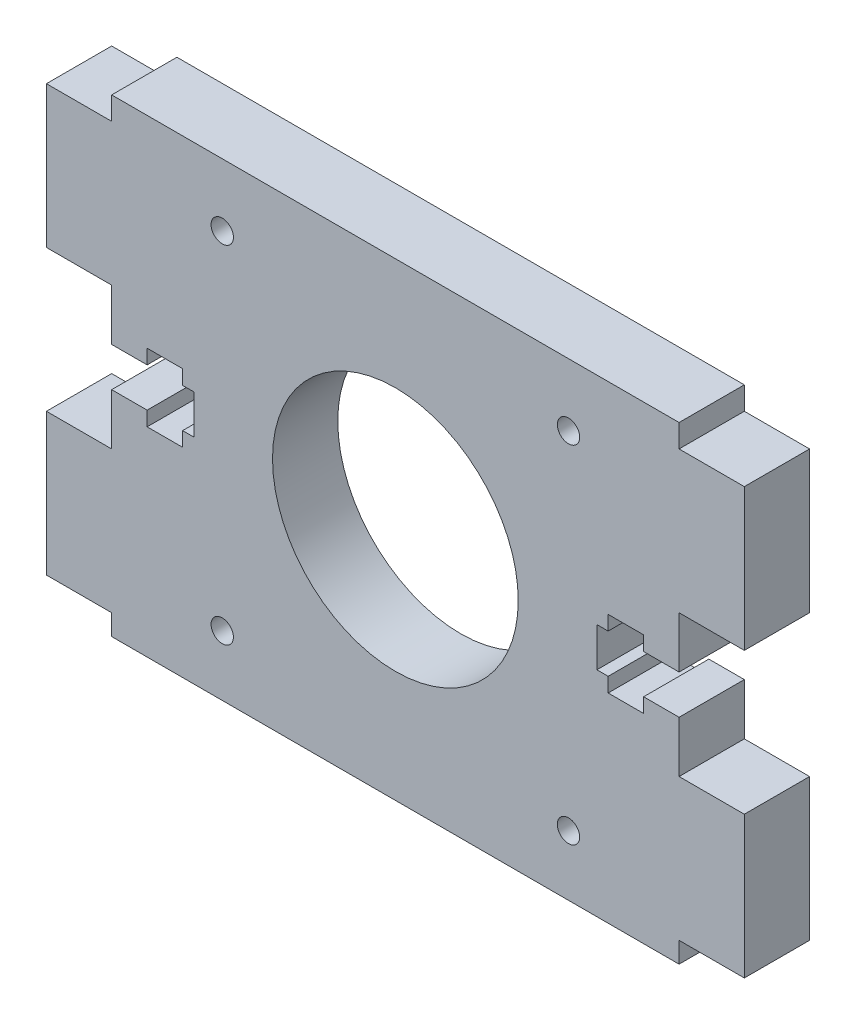
SolidWorks part; units mm, degrees
ref_plane "Front Plane" through (0, 0, 0) normal (0, 0, 1) x (1, 0, 0)
ref_plane "Top Plane" through (0, 0, 0) normal (0, 1, 0) x (1, 0, 0)
ref_plane "Right Plane" through (0, 0, 0) normal (1, 0, 0) x (0, 0, -1)
sketch "Sketch1" plane through (0, 0, 0) normal (0, 0, 1) x (1, 0, 0)
  line L0 (25.4, -0.1) -> (-25.4, -0.1) construction
  line L1 (25.4, -21) -> (-25.4, -21)
  line L2 (25.4, -21) -> (25.4, -19.15)
  line L3 (25.4, 21) -> (-25.4, 21)
  line L4 (-25.4, -6.45) -> (-25.4, 6.25)
  line L5 (25.4, -21) -> (-25.4, 21) construction
  line L6 (25.4, 21) -> (-25.4, -21) construction
  line L7 (0, 21) -> (0, -21) construction
  line L8 (-25.4, 18.95) -> (-25.4, 21)
  line L9 (-31.242, 6.25) -> (-25.4, 6.25)
  line L10 (-31.242, 6.25) -> (-31.242, 18.95)
  line L11 (-31.242, 18.95) -> (-25.4, 18.95)
  line L12 (-31.242, -19.15) -> (-25.4, -6.45) construction
  line L13 (-31.242, 6.25) -> (-25.4, 18.95) construction
  line L14 (-31.242, 18.95) -> (-25.4, 6.25) construction
  line L15 (-31.242, -6.45) -> (-25.4, -19.15) construction
  line L16 (-31.242, -19.15) -> (-25.4, -19.15)
  line L17 (-31.242, -6.45) -> (-31.242, -19.15)
  line L18 (-31.242, -6.45) -> (-25.4, -6.45)
  line L19 (-25.4, -21) -> (-25.4, -19.15)
  line L20 (25.4, 18.95) -> (25.4, 21)
  line L21 (25.4, -21) -> (25.4, -19.15)
  line L22 (31.242, -6.45) -> (25.4, -19.15) construction
  line L23 (31.242, 18.95) -> (25.4, 6.25) construction
  line L24 (31.242, 6.25) -> (25.4, 18.95) construction
  line L25 (31.242, -19.15) -> (25.4, -6.45) construction
  line L26 (31.242, -6.45) -> (25.4, -6.45)
  line L27 (31.242, -6.45) -> (31.242, -19.15)
  line L28 (31.242, -19.15) -> (25.4, -19.15)
  line L29 (31.242, 18.95) -> (25.4, 18.95)
  line L30 (31.242, 6.25) -> (31.242, 18.95)
  line L31 (31.242, 6.25) -> (25.4, 6.25)
  line L32 (25.4, -6.45) -> (25.4, 6.25)
  line L33 (25.4, 18.95) -> (25.4, 21)
  line L34 (25.4, -6.45) -> (25.4, 6.25)
  line L35 (-25.4, 15.4) -> (25.4, 15.4) construction
  circle A0 centre (-15.5, 15.4) radius 1
  circle A1 centre (15.5, 15.4) radius 1
  circle A2 centre (-15.5, -15.6) radius 1
  circle A3 centre (15.5, -15.6) radius 1
  circle A4 centre (0, 0) radius 11
  point P0 (0, 0)
  point P10 (-28.321, 12.6)
  point P19 (-28.321, -12.8)
  point P28 (28.321, -12.8)
  point P29 (28.321, 12.6)
  dimension "D7" = 2
  dimension "D8" = 15.5
  dimension "D9" = 22
  dimension "D1" = 42
  dimension "D2" = 50.8
  dimension "D3" = 12.7
  dimension "D4" = 5.842
  dimension "D5" = 12.7
  dimension "D6" = 15.5
extrude "Boss-Extrude1" add sketch "Sketch1" along normal blind 5.842 contours L26 L32 L31 L30 L29 L20 L3 L8 L11 L10 L9 L4 L18 L17 L16 L19 L1 L2 L28 L27 A3 A1 A0 A2
sketch "Sketch2" plane through (0, 0, 5.842) normal (0, 0, 1) x (1, 0, 0)
  line L0 (0, 21) -> (0, -21) construction
  line L1 (25.4, 21) -> (-25.4, 21) construction
  line L2 (25.4, -21) -> (-25.4, -21) construction
  line L3 (25.4, -0.1) -> (-25.4, -0.1) construction
  line L4 (25.4, -6.45) -> (25.4, 6.25) construction
  line L5 (-25.4, -6.45) -> (-25.4, 6.25) construction
  line L6 (-22.225, 1.6526) -> (-22.225, 2.948)
  line L7 (-22.225, -1.8526) -> (-25.4, -1.8526)
  line L8 (-19.05, 1.6526) -> (-19.05, 2.948)
  line L9 (-22.225, 1.6526) -> (-25.4, 1.6526)
  line L10 (-25.4, -1.8526) -> (-25.4, 1.6526)
  line L11 (-22.225, -1.8526) -> (-25.4, 1.6526) construction
  line L12 (-22.225, 1.6526) -> (-25.4, -1.8526) construction
  line L13 (-19.05, -3.148) -> (-22.225, -3.148)
  line L14 (-19.05, -3.148) -> (-19.05, -1.8526)
  line L15 (-19.05, 2.948) -> (-22.225, 2.948)
  line L16 (-22.225, -3.148) -> (-22.225, -1.8526)
  line L17 (-19.05, -3.148) -> (-22.225, 2.948) construction
  line L18 (-19.05, 2.948) -> (-22.225, -3.148) construction
  line L19 (-18.042, -1.8526) -> (-19.05, -1.8526)
  line L20 (-18.042, -1.8526) -> (-18.042, 1.6526)
  line L21 (-18.042, 1.6526) -> (-19.05, 1.6526)
  line L22 (18.042, 1.6526) -> (19.05, -1.8526) construction
  line L23 (-18.042, -1.8526) -> (-19.05, 1.6526) construction
  line L24 (-18.042, 1.6526) -> (-19.05, -1.8526) construction
  line L25 (18.042, -1.8526) -> (19.05, 1.6526) construction
  line L26 (19.05, 2.948) -> (22.225, -3.148) construction
  line L27 (19.05, -3.148) -> (22.225, 2.948) construction
  line L28 (22.225, 1.6526) -> (25.4, -1.8526) construction
  line L29 (22.225, -1.8526) -> (25.4, 1.6526) construction
  line L30 (18.042, 1.6526) -> (19.05, 1.6526)
  line L31 (18.042, -1.8526) -> (18.042, 1.6526)
  line L32 (18.042, -1.8526) -> (19.05, -1.8526)
  line L33 (22.225, -3.148) -> (22.225, -1.8526)
  line L34 (19.05, 2.948) -> (22.225, 2.948)
  line L35 (19.05, -3.148) -> (19.05, -1.8526)
  line L36 (19.05, -3.148) -> (22.225, -3.148)
  line L37 (25.4, -1.8526) -> (25.4, 1.6526)
  line L38 (22.225, 1.6526) -> (25.4, 1.6526)
  line L39 (19.05, 1.6526) -> (19.05, 2.948)
  line L40 (22.225, -1.8526) -> (25.4, -1.8526)
  line L41 (22.225, 1.6526) -> (22.225, 2.948)
  point P12 (-23.8125, -0.1)
  point P17 (-20.6375, -0.1)
  point P22 (-18.546, -0.1)
  point P39 (18.546, -0.1)
  point P40 (20.6375, -0.1)
  point P41 (23.8125, -0.1)
  dimension "D1" = 3.175
  dimension "D2" = 3.5052
  dimension "D3" = 6.096
  dimension "D4" = 3.175
  dimension "D5" = 3.5052
  dimension "D6" = 1.008
extrude "Cut-Extrude1" cut sketch "Sketch2" against normal through all
equation "\"D6@Sketch2\"=0.5-(0.23+0.125+0.125)+0.5mm"
